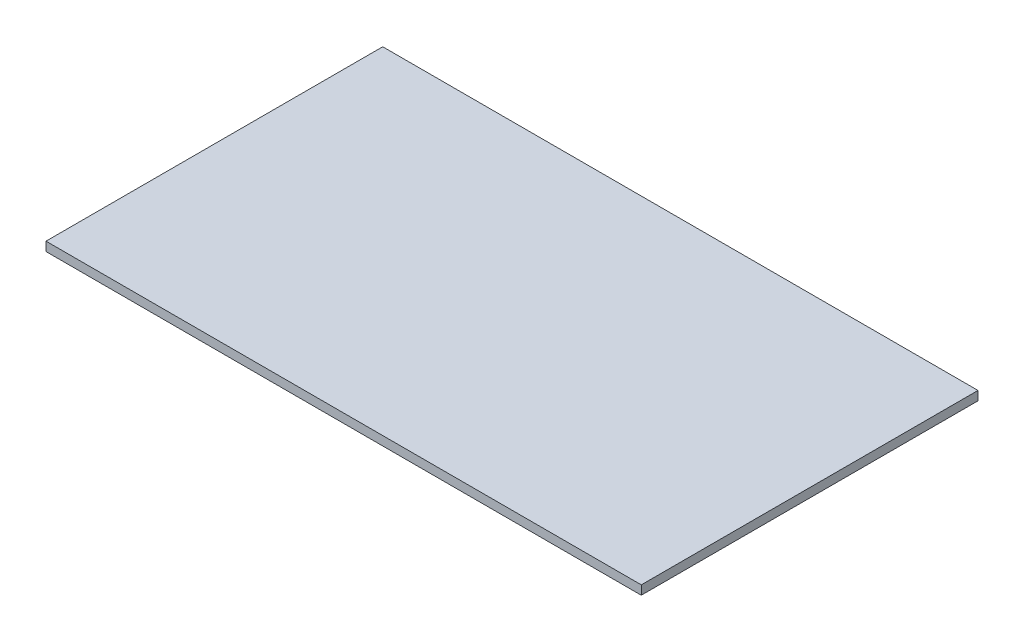
SolidWorks part; units mm, degrees
ref_plane "Front Plane" through (0, 0, 0) normal (0, 0, 1) x (1, 0, 0)
ref_plane "Top Plane" through (0, 0, 0) normal (0, 1, 0) x (1, 0, 0)
ref_plane "Right Plane" through (0, 0, 0) normal (1, 0, 0) x (0, 0, -1)
sketch "Sketch1" plane through (0, 0, 0) normal (0, 0, 1) x (1, 0, 0)
  line L1 (0, 0) -> (198, 0)
  line L2 (0, 0) -> (0, 3)
  line L3 (0, 3) -> (198, 3)
  line L4 (198, 0) -> (198, 3)
  dimension "D1" = 198
  dimension "D2" = 3
extrude "Profile" add sketch "Sketch1" along normal blind 112
equation "\"Profile_Depth\"= 112mm"
equation "\"D1@Profile\" = \"Profile_Depth\""
equation "\"Profile_Sketch_1\"= 198mm"
equation "\"D1@Sketch1\" = \"Profile_Sketch_1\""
equation "\"Profile_Sketch_2\"= 3mm"
equation "\"D2@Sketch1\" = \"Profile_Sketch_2\""
equation "\"EnvelopeWidth\"= 198mm"
equation "\"EnvelopeHeight\"= 3mm"
